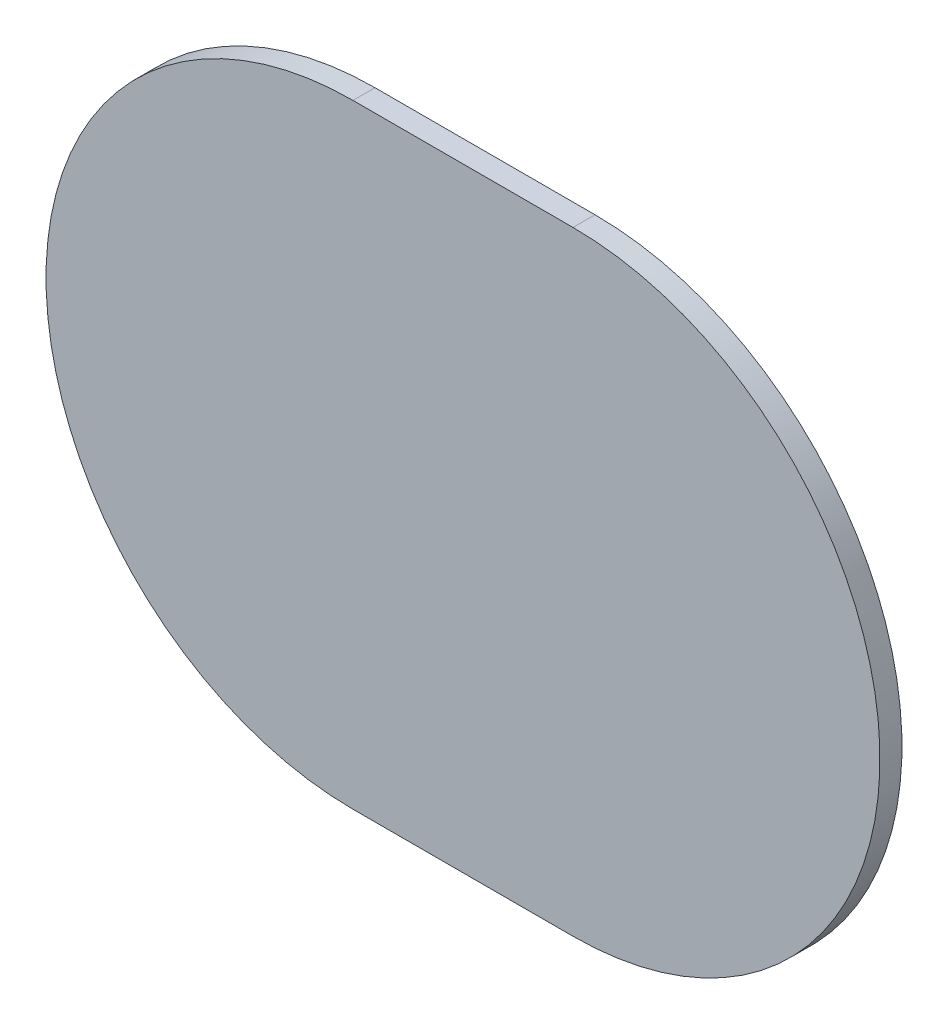
SolidWorks part; units mm, degrees
ref_plane "前视基准面" through (0, 0, 0) normal (0, 0, 1) x (1, 0, 0)
ref_plane "上视基准面" through (0, 0, 0) normal (0, 1, 0) x (1, 0, 0)
ref_plane "右视基准面" through (0, 0, 0) normal (1, 0, 0) x (0, 0, -1)
other "Configuration Table"
sketch "草图1" plane through (0, 0, 0) normal (0, 0, 1) x (1, 0, 0)
  line L0 (0, 27.9) -> (-20, 27.9)
  line L1 (-20, -27.9) -> (0, -27.9)
  line L2 (0, 28) -> (-20, 28)
  line L3 (-20, -28) -> (0, -28)
  line L4 (0, 28) -> (-20, 28)
  line L5 (-20, -28) -> (0, -28)
  arc A0 (0, -27.9) -> (0, 27.9) centre (0, 0) ccw
  arc A1 (-20, 27.9) -> (-20, -27.9) centre (-20, 0) ccw
  arc A2 (-20, 28) -> (-20, -28) centre (-20, 0) ccw
  arc A3 (0, -28) -> (0, 28) centre (0, 0) ccw
  arc A4 (-20, 28) -> (-20, -28) centre (-20, 0) ccw
  arc A5 (0, -28) -> (0, 28) centre (0, 0) ccw
  dimension "D1" = 0
extrude "凸台-拉伸1" add sketch "草图1" along normal blind 2 contours A0 L0 A1 L1
